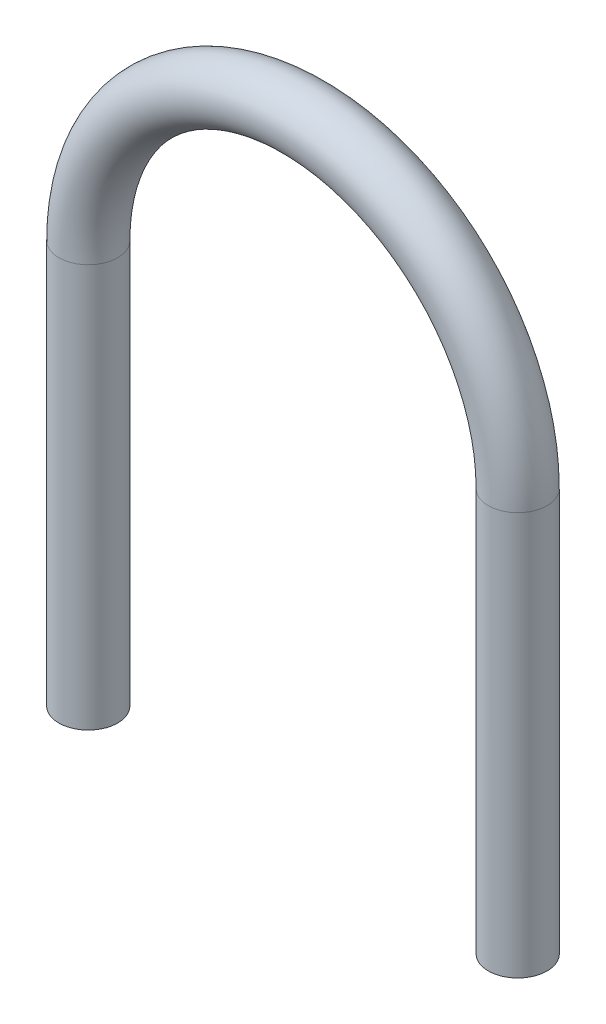
SolidWorks part; units mm, degrees
ref_plane "Alzado" through (0, 0, 0) normal (0, 0, 1) x (1, 0, 0)
ref_plane "Planta" through (0, 0, 0) normal (0, 1, 0) x (1, 0, 0)
ref_plane "Vista lateral" through (0, 0, 0) normal (1, 0, 0) x (0, 0, -1)
sketch "Croquis1" plane through (0, 0, 0) normal (0, 1, 0) x (1, 0, 0)
  line L0 (-28.969, 0) -> (28.969, 0) construction
  circle A0 centre (28.969, 0) radius 3.969
  point P4 (0, 0)
  dimension "D2" = 7.938
  dimension "D1" = 57.938
sketch "Croquis2" plane through (0, 0, 0) normal (0, 0, 1) x (1, 0, 0)
  line L0 (0, 54.369) -> (0, 0) construction
  line L1 (-28.969, 54.369) -> (-28.969, 0)
  line L2 (28.969, 54.369) -> (28.969, 0)
  line L3 (-28.969, 0) -> (28.969, 0) construction
  line L4 (32.938, 0) -> (25, 0) construction
  arc A0 (28.969, 54.369) -> (-28.969, 54.369) centre (0, 54.369) ccw
  arc A1 (28.969, 54.369) -> (-28.969, 54.369) centre (0, 54.369) cw construction
  point P8 (0, 25.4)
  dimension "D1" = 57.938
sweep "Barrer1" add profiles "Croquis1" path "Croquis2"
equation "\"diametrodetuberia\"=0.05"
equation "\"D1@Croquis1\"=\"diametrodetuberia\"+\"diamBirlo\""
equation "\"D1@Croquis2\"=\"diametrodetuberia\"+\"diamBirlo\""
equation "\"diamBirlo\"=0.007938"
equation "\"D2@Croquis1\"=\"diamBirlo\""
